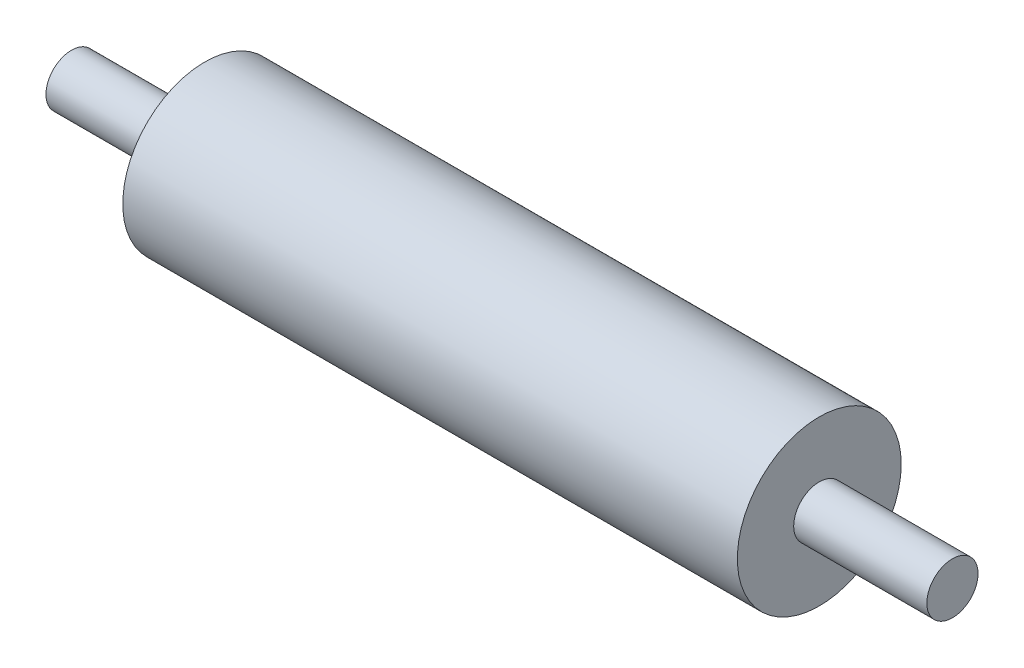
SolidWorks part; units mm, degrees
ref_plane "Front Plane" through (0, 0, 0) normal (0, 0, 1) x (1, 0, 0)
ref_plane "Top Plane" through (0, 0, 0) normal (0, 1, 0) x (1, 0, 0)
ref_plane "Right Plane" through (0, 0, 0) normal (1, 0, 0) x (0, 0, -1)
sketch "Sketch1" plane through (0, 0, 0) normal (1, 0, 0) x (0, 0, -1)
  circle A0 centre (0, 0) radius 8
  dimension "D1" = 16
extrude "Boss-Extrude1" add sketch "Sketch1" along normal blind 30
sketch "Sketch2" plane through (30, 0, 0) normal (1, 0, 0) x (0, 0, -1)
  circle A0 centre (0, 0) radius 2.5
  dimension "D1" = 5
extrude "Boss-Extrude2" add sketch "Sketch2" along normal blind 13
mirror "Mirror1" about plane through (0, 0, 0) normal (1, 0, 0) of "Boss-Extrude1", "Boss-Extrude2"
